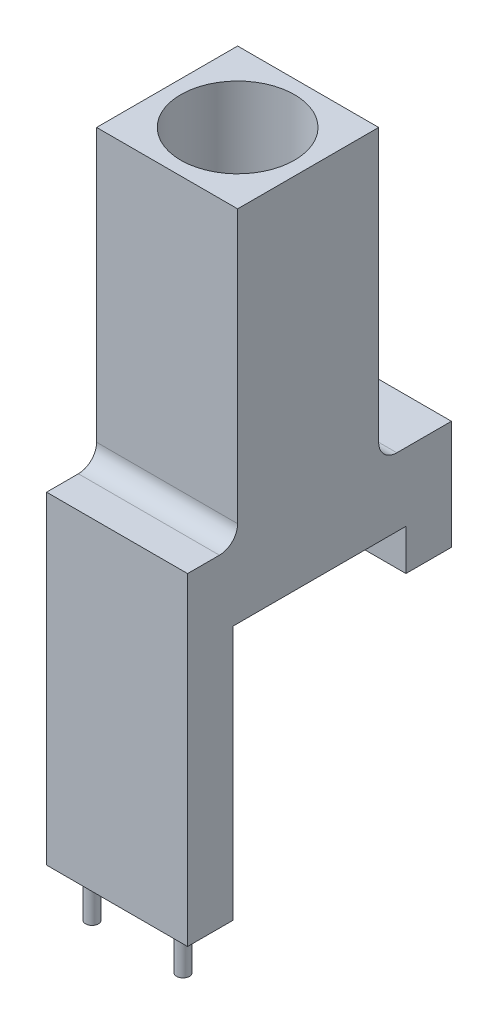
SolidWorks part; units mm, degrees
ref_plane "Front Plane" through (0, 0, 0) normal (0, 0, 1) x (1, 0, 0)
ref_plane "Top Plane" through (0, 0, 0) normal (0, 1, 0) x (1, 0, 0)
ref_plane "Right Plane" through (0, 0, 0) normal (1, 0, 0) x (0, 0, -1)
sketch "Sketch1" plane through (0, 0, 0) normal (0, 0, 1) x (1, 0, 0)
  line L0 (-15.5, 107.5) -> (-15.5, 28.5657)
  line L1 (15.5, 28.5657) -> (15.5, 107.5)
  line L2 (15.5, 107.5) -> (-15.5, 107.5)
  arc A0 (15.5, 28.5657) -> (-15.5, 28.5657) centre (0, 0) ccw
  dimension "D1" = 65
  dimension "D2" = 31
  dimension "D3" = 107.5
extrude "Boss-Extrude1" add sketch "Sketch1" along normal blind 31
sketch "Sketch3" plane through (0, 107.5, 0) normal (0, 1, 0) x (1, 0, 0)
  circle A0 centre (0, -15.5) radius 12.5
  dimension "D1" = 25
  dimension "D2" = 15.5
extrude "Cut-Extrude1" cut sketch "Sketch3" against normal through all
sketch "Sketch4" plane through (0, 0, 31) normal (0, 0, 1) x (1, 0, 0)
  line L0 (-15.5, 107.5) -> (-15.5, 28.5657) construction
  line L1 (-15.5, 43.5657) -> (15.5, 43.5657)
  line L2 (-15.5, 43.5657) -> (-15.5, 28.5657)
  line L3 (-15.5, 28.5657) -> (15.5, 28.5657)
  line L4 (15.5, 43.5657) -> (15.5, 28.5657)
  line L5 (15.5, 28.5657) -> (15.5, 107.5) construction
  dimension "D2" = 15
extrude "Boss-Extrude2" add sketch "Sketch4" along normal blind 11
sketch "Sketch5" plane through (0, 28.5657, 0) normal (0, -1, 0) x (1, 0, 0)
  line L0 (15.5, 42) -> (15.5, 31) construction
  line L1 (-15.5, 42) -> (15.5, 42)
  line L2 (-15.5, 42) -> (-15.5, 32)
  line L3 (-15.5, 32) -> (15.5, 32)
  line L4 (15.5, 42) -> (15.5, 32)
  dimension "D1" = 10
extrude "Boss-Extrude3" add sketch "Sketch5" along normal blind 56
sketch "Sketch6" plane through (0, -27.4343, 0) normal (0, -1, 0) x (1, 0, 0)
  line L0 (15.5, 42) -> (-15.5, 42) construction
  line L1 (0, 42) -> (0, 32) construction
  line L2 (-15.5, 32) -> (15.5, 32) construction
  circle A0 centre (-10, 37.5) radius 1.4
  circle A1 centre (10, 37.5) radius 1.4
  dimension "D2" = 2.8
  dimension "D1" = 4.5
  dimension "D3" = 10
extrude "Boss-Extrude4" add sketch "Sketch6" along normal blind 10
sketch "Sketch7" plane through (0, 0, 0) normal (0, 0, -1) x (-1, 0, 0)
  line L0 (15.5, 107.5) -> (15.5, 28.5657) construction
  line L1 (-15.5, 28.5657) -> (15.5, 28.5657)
  line L2 (-15.5, 28.5657) -> (-15.5, 43.5657)
  line L3 (-15.5, 43.5657) -> (15.5, 43.5657)
  line L4 (15.5, 28.5657) -> (15.5, 43.5657)
  dimension "D1" = 15
extrude "Boss-Extrude5" add sketch "Sketch7" along normal blind 16
sketch "Sketch8" plane through (0, 28.5657, 0) normal (0, -1, 0) x (1, 0, 0)
  line L0 (15.5, -16) -> (15.5, 0) construction
  line L1 (-15.5, -16) -> (15.5, -16)
  line L2 (-15.5, -16) -> (-15.5, -6)
  line L3 (-15.5, -6) -> (15.5, -6)
  line L4 (15.5, -16) -> (15.5, -6)
  dimension "D1" = 10
extrude "Boss-Extrude6" add sketch "Sketch8" along normal blind 9
fillet "Fillet1" radius 4 2 edges at (0, 43.5657, 31) (0, 43.5657, 0)
